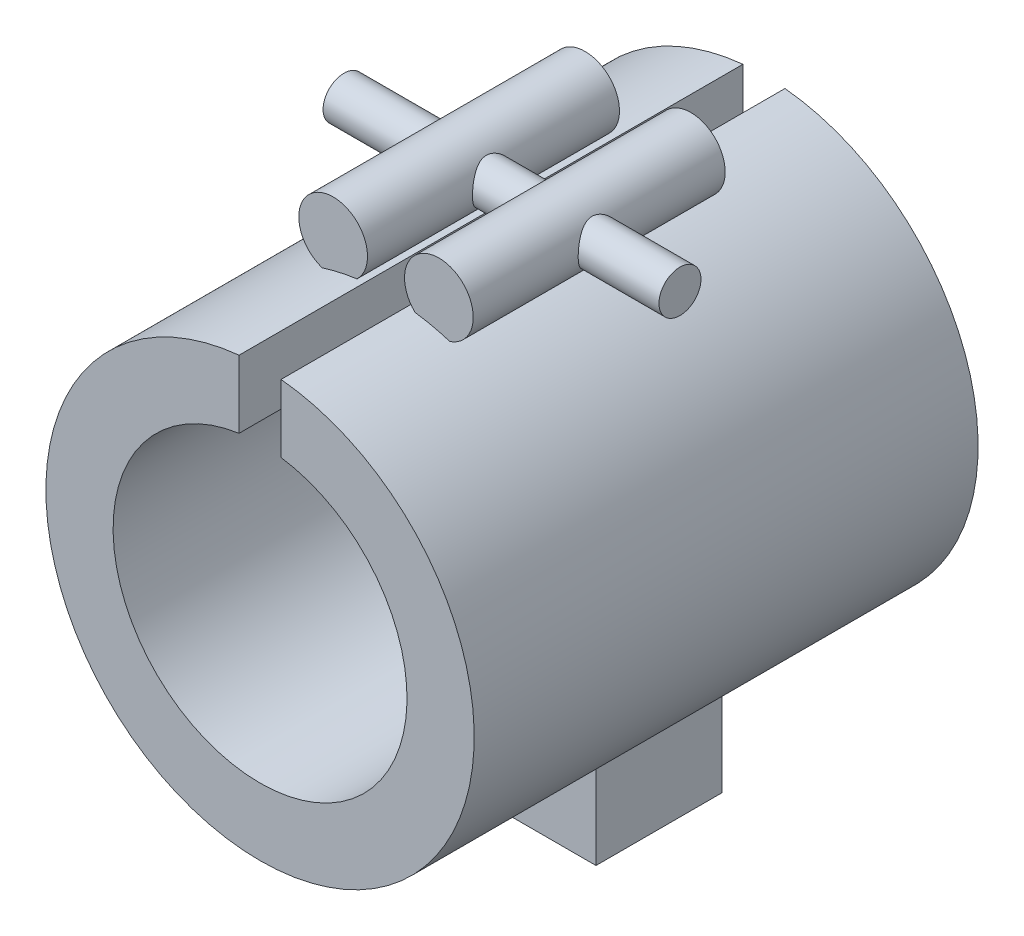
SolidWorks part; units mm, degrees
ref_plane "Front Plane" through (0, 0, 0) normal (0, 0, 1) x (1, 0, 0)
ref_plane "Top Plane" through (0, 0, 0) normal (0, 1, 0) x (1, 0, 0)
ref_plane "Right Plane" through (0, 0, 0) normal (1, 0, 0) x (0, 0, -1)
sketch "Sketch1" plane through (0, 0, 0) normal (0, 0, 1) x (1, 0, 0)
  line L0 (-2.5, 25.3772) -> (-2.5, 17.3205)
  line L1 (0, 0) -> (0, 34.2254) construction
  line L2 (2.5, 25.3772) -> (2.5, 17.3205)
  arc A0 (-2.5, 25.3772) -> (2.5, 25.3772) centre (0, 0) ccw
  arc A1 (-2.5, 17.3205) -> (2.5, 17.3205) centre (0, 0) ccw
  dimension "D1" = 35
  dimension "D2" = 8
  dimension "D3" = 5
extrude "Boss-Extrude1" add sketch "Sketch1" along normal mid plane 60
sketch "Sketch2" plane through (0, 0, 0) normal (0, 0, 1) x (1, 0, 0)
  line L0 (0, 0) -> (0, 40.0287) construction
  circle A0 centre (6.2935, 28.2115) radius 4.0912
  circle A1 centre (-6.2935, 28.2115) radius 4.0912
  arc A2 (-2.5, 25.3772) -> (2.5, 25.3772) centre (0, 0) ccw construction
  arc A3 (-2.5, 25.3772) -> (2.5, 25.3772) centre (0, 0) ccw construction
  dimension "D1" = 2.8343
  dimension "D3" = 8.1825
  dimension "D2" = 12.5871
extrude "Boss-Extrude2" add sketch "Sketch2" along normal mid plane 30
sketch "Sketch3" plane through (0, 0, 0) normal (0, 0, 1) x (1, 0, 0)
  line L0 (0, 0) -> (0, -23.0171) construction
  line L1 (-10, -23.0171) -> (10, -23.0171)
  line L2 (-10, -23.0171) -> (-10, -36)
  line L3 (-10, -36) -> (10, -36)
  line L4 (10, -23.0171) -> (10, -36)
  arc A0 (-2.5, 25.3772) -> (2.5, 25.3772) centre (0, 0) ccw construction
  dimension "D2" = 36
  dimension "D1" = 20
extrude "Boss-Extrude3" add sketch "Sketch3" against normal blind 15
sketch "Sketch4" plane through (0, 0, 0) normal (0, 0, 1) x (1, 0, 0)
  circle A0 centre (0, -38.1274) radius 3.5547
sketch "Sketch5" plane through (0, 0, 0) normal (1, 0, 0) x (0, 0, -1)
  circle A0 centre (0, 28.2115) radius 2.5
  dimension "D1" = 5
extrude "Boss-Extrude5" add sketch "Sketch5" along normal blind 20 and the other way blind 20
sketch "Sketch6" plane through (-20, 0, 0) normal (-1, 0, 0) x (0, 0, 1)
  circle A0 centre (0, 28.2115) radius 5
  circle A1 centre (0, 28.2115) radius 2.5 construction
  dimension "D1" = 10
